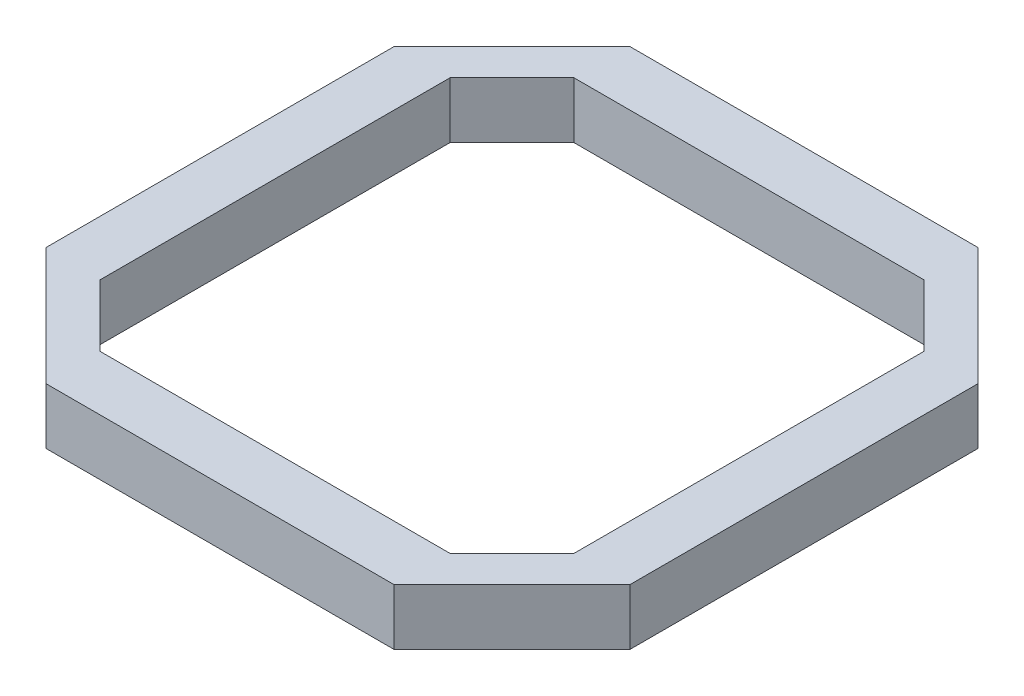
SolidWorks part; units mm, degrees
ref_plane "Front Plane" through (0, 0, 0) normal (0, 0, 1) x (1, 0, 0)
ref_plane "Top Plane" through (0, 0, 0) normal (0, 1, 0) x (1, 0, 0)
ref_plane "Right Plane" through (0, 0, 0) normal (1, 0, 0) x (0, 0, -1)
sketch "Sketch2" plane through (0, 0, 0) normal (0, 1, 0) x (1, 0, 0)
  line L0 (-15.5, -26) -> (15.5, -26)
  line L1 (15.5, -26) -> (26, -15.5)
  line L2 (26, -15.5) -> (26, 15.5)
  line L3 (26, 15.5) -> (15.5, 26)
  line L4 (15.5, 26) -> (-15.5, 26)
  line L5 (-15.5, 26) -> (-26, 15.5)
  line L6 (-26, 15.5) -> (-26, -15.5)
  line L7 (-26, -15.5) -> (-15.5, -26)
  dimension "D1" = 31
  dimension "D2" = 52
  dimension "D3" = 52
  dimension "D4" = 31
  dimension "D5" = 10.5
  dimension "D6" = 10.5
  dimension "D7" = 26
  dimension "D8" = 26
extrude "Boss-Extrude1" add sketch "Sketch2" along normal blind 5
sketch "Sketch3" plane through (0, 5, 0) normal (0, 1, 0) x (1, 0, 0)
  line L0 (-21.1, -15.6) -> (-21.1, 15.6)
  line L1 (-15.6, 21.1) -> (15.6, 21.1)
  line L2 (15.6, 21.1) -> (21.1, 15.6)
  line L3 (21.1, 15.6) -> (21.1, -15.6)
  line L4 (21.1, -15.6) -> (15.6, -21.1)
  line L5 (15.6, -21.1) -> (-15.6, -21.1)
  line L6 (-15.6, -21.1) -> (-21.1, -15.6)
  line L7 (-21.1, 15.6) -> (-15.6, 21.1)
  dimension "D1" = 42.2
  dimension "D2" = 42.2
  dimension "D3" = 135
  dimension "D4" = 31.2
  dimension "D5" = 31.2
  dimension "D6" = 21.1
  dimension "D7" = 21.1
extrude "Cut-Extrude1" cut sketch "Sketch3" against normal blind 5
